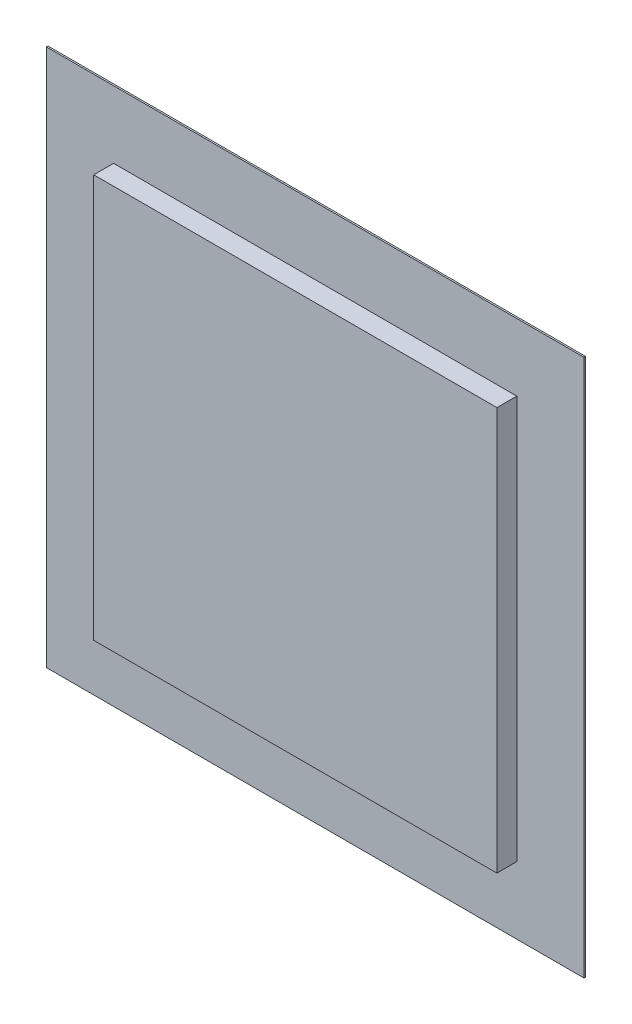
SolidWorks part; units mm, degrees
ref_plane "Front Plane" through (0, 0, 0) normal (0, 0, 1) x (1, 0, 0)
ref_plane "Top Plane" through (0, 0, 0) normal (0, 1, 0) x (1, 0, 0)
ref_plane "Right Plane" through (0, 0, 0) normal (1, 0, 0) x (0, 0, -1)
sketch "Sketch1" plane through (0, 0, 0) normal (0, 0, 1) x (1, 0, 0)
  line L0 (-50, -50) -> (50, -50)
  line L1 (50, -50) -> (50, 50)
  line L2 (50, 50) -> (-50, 50)
  line L3 (-50, 50) -> (-50, -50)
extrude "Boss-Extrude1" add sketch "Sketch1" along normal blind 0.3
sketch "Sketch2" plane through (0, 0, 0) normal (0, 0, 1) x (1, 0, 0)
  line L0 (-37.5, -37.5) -> (37.5, -37.5)
  line L1 (37.5, -37.5) -> (37.5, 37.5)
  line L2 (37.5, 37.5) -> (-37.5, 37.5)
  line L3 (-37.5, 37.5) -> (-37.5, -37.5)
extrude "Boss-Extrude2" add sketch "Sketch2" along normal blind 4
